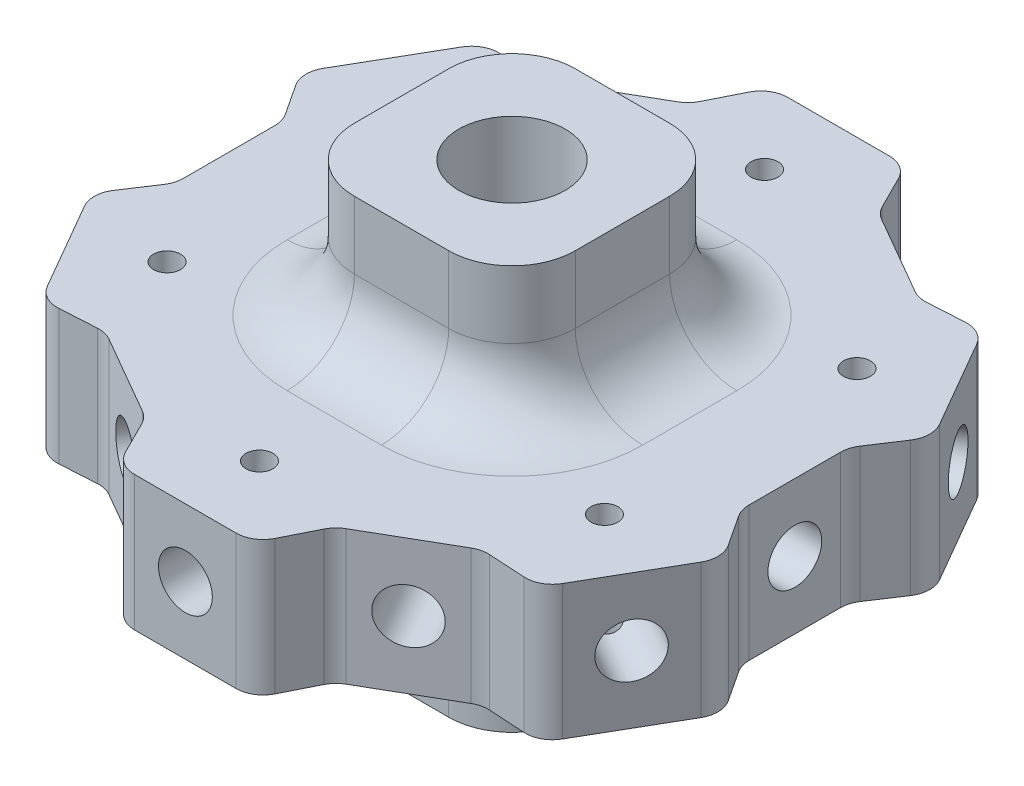
SolidWorks part; units mm, degrees
ref_plane "Front Plane" through (0, 0, 0) normal (0, 0, 1) x (1, 0, 0)
ref_plane "Top Plane" through (0, 0, 0) normal (0, 1, 0) x (1, 0, 0)
ref_plane "Right Plane" through (0, 0, 0) normal (1, 0, 0) x (0, 0, -1)
ref_axis "Axis1" through (0, 60, 0) along (0, -1, 0)
sketch "Sketch1" plane through (0, 0, 0) normal (0, 1, 0) x (1, 0, 0)
  line L0 (-5, 24.25) -> (5, 24.25)
  line L1 (0, 0) -> (12.5, 21.6506) construction
  line L2 (7.0359, 20.1865) -> (13.9641, 16.1865)
  line L3 (0, 0) -> (0, 25) construction
  line L4 (5, 24.25) -> (7.0359, 20.1865)
  line L5 (18.5011, 16.4551) -> (23.5011, 7.7949)
  line L6 (21, 4) -> (21, -4)
  line L7 (23.5011, -7.7949) -> (18.5011, -16.4551)
  line L8 (13.9641, -16.1865) -> (7.0359, -20.1865)
  line L9 (5, -24.25) -> (-5, -24.25)
  line L10 (-7.0359, -20.1865) -> (-13.9641, -16.1865)
  line L11 (-18.5011, -16.4551) -> (-23.5011, -7.7949)
  line L12 (-21, -4) -> (-21, 4)
  line L13 (-23.5011, 7.7949) -> (-18.5011, 16.4551)
  line L14 (-13.9641, 16.1865) -> (-7.0359, 20.1865)
  line L15 (-7.0359, 20.1865) -> (-5, 24.25)
  line L16 (13.9641, 16.1865) -> (18.5011, 16.4551)
  line L17 (23.5011, 7.7949) -> (21, 4)
  line L18 (21, -4) -> (23.5011, -7.7949)
  line L19 (18.5011, -16.4551) -> (13.9641, -16.1865)
  line L20 (7.0359, -20.1865) -> (5, -24.25)
  line L21 (-5, -24.25) -> (-7.0359, -20.1865)
  line L22 (-13.9641, -16.1865) -> (-18.5011, -16.4551)
  line L23 (-23.5011, -7.7949) -> (-21, -4)
  line L24 (-21, 4) -> (-23.5011, 7.7949)
  line L25 (-18.5011, 16.4551) -> (-13.9641, 16.1865)
  circle A0 centre (0, 0) radius 25 construction
  point P9 (10.5, 18.1865)
  point P11 (0, 24.25)
  point P34 (0, 0)
  point P55 (0, 0)
  dimension "D1" = 50
  dimension "D2" = 30
  dimension "D3" = 10
  dimension "D4" = 8
  dimension "D5" = 21
  dimension "D6" = 24.25
  dimension "D8" = 6
  dimension "D7" = 6
extrude "Boss-Extrude1" add sketch "Sketch1" along normal mid plane 10
sketch "Sketch5" plane through (0, 0, 0) normal (0, 1, 0) x (1, 0, 0)
  line L1 (-8.2, 8.2) -> (8.2, 8.2)
  line L2 (-8.2, 8.2) -> (-8.2, -8.2)
  line L3 (-8.2, -8.2) -> (8.2, -8.2)
  line L4 (8.2, 8.2) -> (8.2, -8.2)
  line L5 (-8.2, 8.2) -> (8.2, -8.2) construction
  line L6 (-8.2, -8.2) -> (8.2, 8.2) construction
  circle A0 centre (0, 0) radius 5.04
  point P0 (0, 0)
  dimension "D2" = 10.08
  dimension "D1" = 16.4
extrude "Boss-Extrude2" add sketch "Sketch5" against normal blind 15 and the other way blind 15
fillet "Fillet1" radius 2 24 edges at (-7.0359, 0, -20.1865) (-5, 0, -24.25) (7.0359, 0, -20.1865) (5, 0, -24.25) (-18.5011, 0, -16.4551) (-13.9641, 0, -16.1865) (-23.5011, 0, -7.7949) (-21, 0, -4) (-21, 0, 4) (-23.5011, 0, 7.7949) (-18.5011, 0, 16.4551) (-13.9641, 0, 16.1865) (-7.0359, 0, 20.1865) (-5, 0, 24.25) (5, 0, 24.25) (7.0359, 0, 20.1865) (13.9641, 0, 16.1865) (18.5011, 0, 16.4551) (23.5011, 0, 7.7949) (21, 0, 4) (21, 0, -4) (23.5011, 0, -7.7949) (18.5011, 0, -16.4551) (13.9641, 0, -16.1865)
fillet "Fillet2" radius 4.7 8 edges at (-8.2, -10, -8.2) (8.2, -10, -8.2) (8.2, -10, 8.2) (-8.2, -10, 8.2) (8.2, 10, -8.2) (8.2, 10, 8.2) (-8.2, 10, -8.2) (-8.2, 10, 8.2)
fillet "Fillet3" radius 5 16 edges at (6.8234, -5, 6.8234) (8.2, -5, 0) (6.8234, -5, -6.8234) (0, -5, -8.2) (-6.8234, -5, -6.8234) (-8.2, -5, 0) (-6.8234, -5, 6.8234) (0, -5, 8.2) (0, 5, 8.2) (6.8234, 5, 6.8234) (8.2, 5, 0) (6.8234, 5, -6.8234) (0, 5, -8.2) (-6.8234, 5, -6.8234) (-8.2, 5, 0) (-6.8234, 5, 6.8234)
sketch "Sketch2" plane through (0, 5, 0) normal (0, 1, 0) x (1, 0, 0)
  line L0 (0, 18.75) -> (0, 0) construction
  circle A0 centre (0, 18.75) radius 1
  circle A1 centre (16.238, 9.375) radius 1
  circle A2 centre (16.238, -9.375) radius 1
  circle A3 centre (0, -18.75) radius 1
  circle A4 centre (-16.238, -9.375) radius 1
  circle A5 centre (-16.238, 9.375) radius 1
  point P17 (0, 0)
  dimension "D1" = 18.75
  dimension "D2" = 2
  dimension "D3" = 6
extrude "Cut-Extrude1" cut sketch "Sketch2" against normal through all
sketch "Sketch3" plane through (0, 0, -24.25) normal (0, 0, -1) x (-1, 0, 0)
  circle A0 centre (0, 0) radius 2
  dimension "D1" = 4
extrude "Cut-Extrude2" cut sketch "Sketch3" against normal blind 5.5
sketch "Sketch4" plane through (10.5, 0, -18.1865) normal (0.5, 0, -0.866) x (-0.866, 0, -0.5)
  circle A0 centre (0, 0) radius 2
  dimension "D1" = 4
extrude "Cut-Extrude3" cut sketch "Sketch4" against normal blind 13
pattern_circular "CirPattern4" count 6 over 360 about axis through (0, 0, 0) along (0, 1, 0) of "Cut-Extrude2", "Cut-Extrude3"
sketch "Sketch6" plane through (0, 0, 8.2) normal (0, 0, 1) x (1, 0, 0)
  line L0 (0, 0) -> (0, -20.7855) construction
  line L3 (-3.5, -15) -> (3.5, -15) construction
  circle A0 centre (0, -10) radius 2.25
  dimension "D1" = 5
  dimension "D2" = 4.5
extrude "Cut-Extrude4" cut sketch "Sketch6" against normal up to next
sketch "Sketch7" plane through (0, 0, 8.2) normal (0, 0, 1) x (1, 0, 0)
  circle A0 centre (0, -10) radius 3.5
  arc A1 (-2.25, -10) -> (2.25, -10) centre (0, -10) ccw construction
  dimension "D1" = 7
extrude "Cut-Extrude5" cut sketch "Sketch7" along normal through all
pattern_circular "CirPattern5" count 2 over 90 about axis through (0, 60, 0) along (0, -1, 0) of "Cut-Extrude4", "Cut-Extrude5"
sketch "Sketch8" plane through (0, 15, 0) normal (0, 1, 0) x (1, 0, 0)
  circle A0 centre (0, 0) radius 3.95
  circle A1 centre (0, 0) radius 5.04 construction
  circle A2 centre (0, 0) radius 5.04
  dimension "D1" = 7.9
extrude "Boss-Extrude3" add sketch "Sketch8" against normal up to surface (10 mm away) up to face at (0, 5, -5.04)
